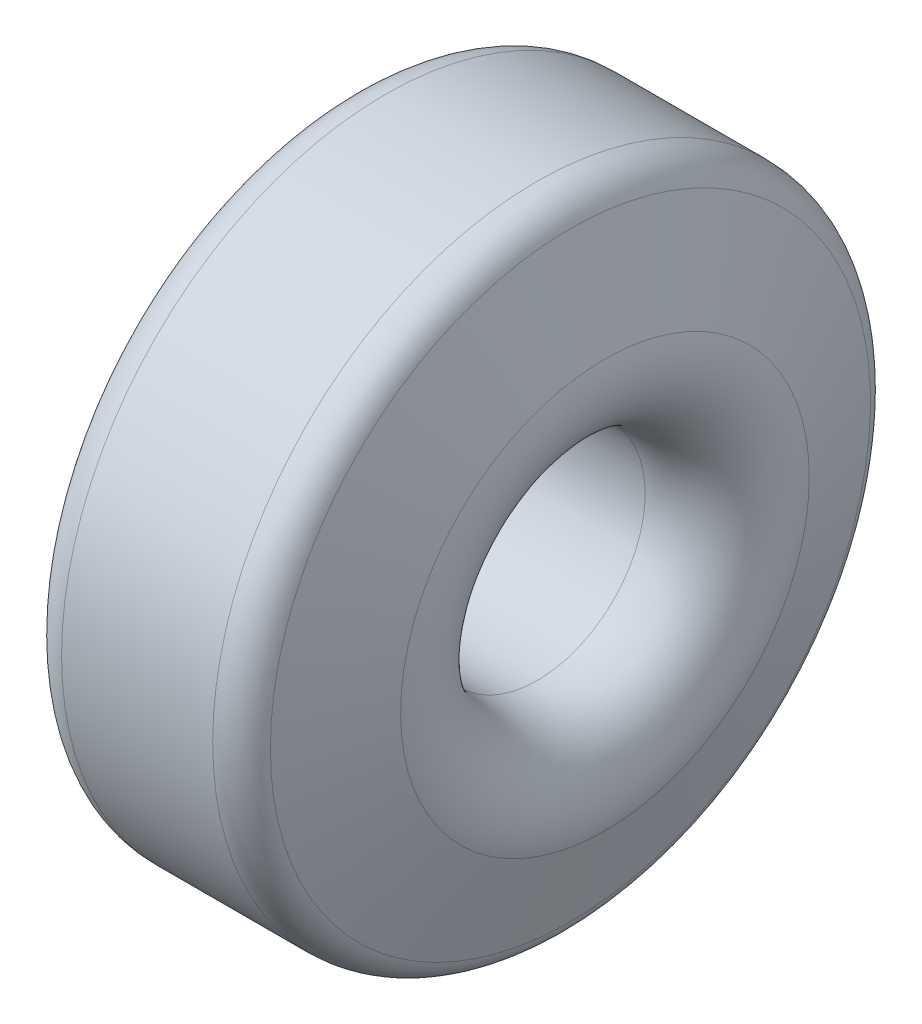
SolidWorks part; units mm, degrees
ref_plane "Спереди" through (0, 0, 0) normal (0, 0, 1) x (1, 0, 0)
ref_plane "Сверху" through (0, 0, 0) normal (0, 1, 0) x (1, 0, 0)
ref_plane "Справа" through (0, 0, 0) normal (1, 0, 0) x (0, 0, -1)
sketch "Эскиз1" plane through (0, 0, 0) normal (0, 0, 1) x (1, 0, 0)
  line L0 (-29.7112, 0) -> (52.5661, 0) construction
  line L1 (2.5942, 8.3391) -> (3.5534, 5.6783)
  line L2 (-2.6966, 8) -> (1.8034, 8)
  line L3 (-2.6966, 8) -> (-2.6966, 5)
  line L4 (-2.6966, 5) -> (1.8034, 5)
  line L5 (1.8034, 8) -> (1.8034, 5)
  line L6 (-2.5651, 3) -> (1.672, 3)
  line L8 (-2.5466, 9) -> (1.6534, 9)
  line L9 (-0.4466, 11.566) -> (-0.4466, 1.1778) construction
  line L10 (-3.4873, 8.3391) -> (-4.4466, 5.6783)
  arc A0 (-3.4873, 8.3391) -> (-2.5466, 9) centre (-2.5466, 8) cw
  arc A1 (1.6534, 9) -> (2.5942, 8.3391) centre (1.6534, 8) cw
  arc A2 (3.5534, 5.6783) -> (1.672, 3) centre (1.672, 5) cw
  arc A3 (-4.4466, 5.6783) -> (-2.5651, 3) centre (-2.5651, 5) ccw
  dimension "D5" = 1
  dimension "D6" = 2
  dimension "D1" = 4.5
  dimension "D2" = 3
  dimension "D3" = 5
  dimension "D4" = 1
  dimension "D7" = 2
  dimension "D8" = 4.2
  dimension "D9" = 8
revolve "Повернуть1" add sketch "Эскиз1" angle 360 about L0
